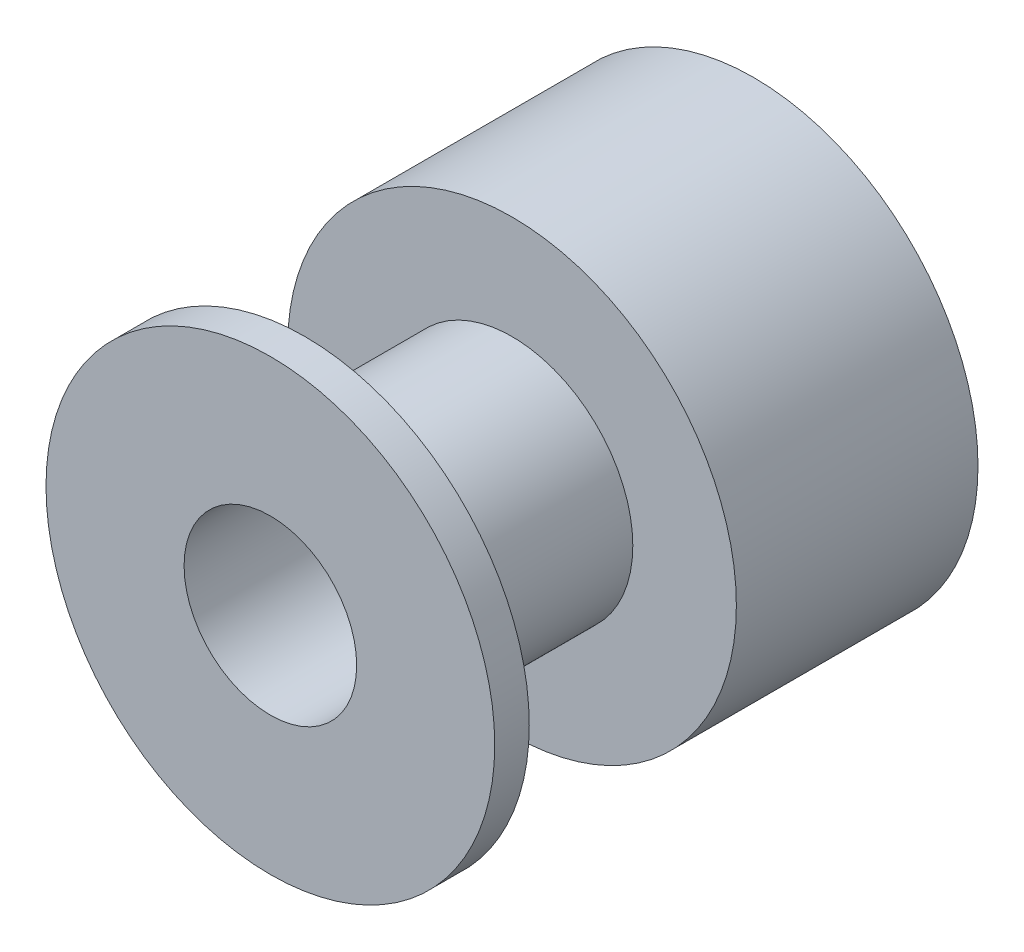
SolidWorks part; units mm, degrees
ref_plane "Спереди" through (0, 0, 0) normal (0, 0, 1) x (1, 0, 0)
ref_plane "Сверху" through (0, 0, 0) normal (0, 1, 0) x (1, 0, 0)
ref_plane "Справа" through (0, 0, 0) normal (1, 0, 0) x (0, 0, -1)
sketch "Эскиз1" plane through (0, 0, 0) normal (0, 0, 1) x (1, 0, 0)
  circle A0 centre (0, 0) radius 6.5
  dimension "D1" = 13
extrude "Бобышка-Вытянуть1" add sketch "Эскиз1" along normal blind 1
sketch "Эскиз2" plane through (0, 0, 0) normal (0, 0, -1) x (-1, 0, 0)
  circle A0 centre (0, 0) radius 3.5
  dimension "D1" = 7
extrude "Бобышка-Вытянуть2" add sketch "Эскиз2" along normal blind 6
sketch "Эскиз3" plane through (0, 0, -6) normal (0, 0, -1) x (-1, 0, 0)
  circle A0 centre (0, 0) radius 6.5
  dimension "D1" = 13
extrude "Бобышка-Вытянуть3" add sketch "Эскиз3" along normal blind 7
sketch "Эскиз4" plane through (0, 0, -13) normal (0, 0, -1) x (-1, 0, 0)
  circle A0 centre (0, 0) radius 2.5
  dimension "D1" = 5
extrude "Вырез-Вытянуть1" cut sketch "Эскиз4" against normal through all
